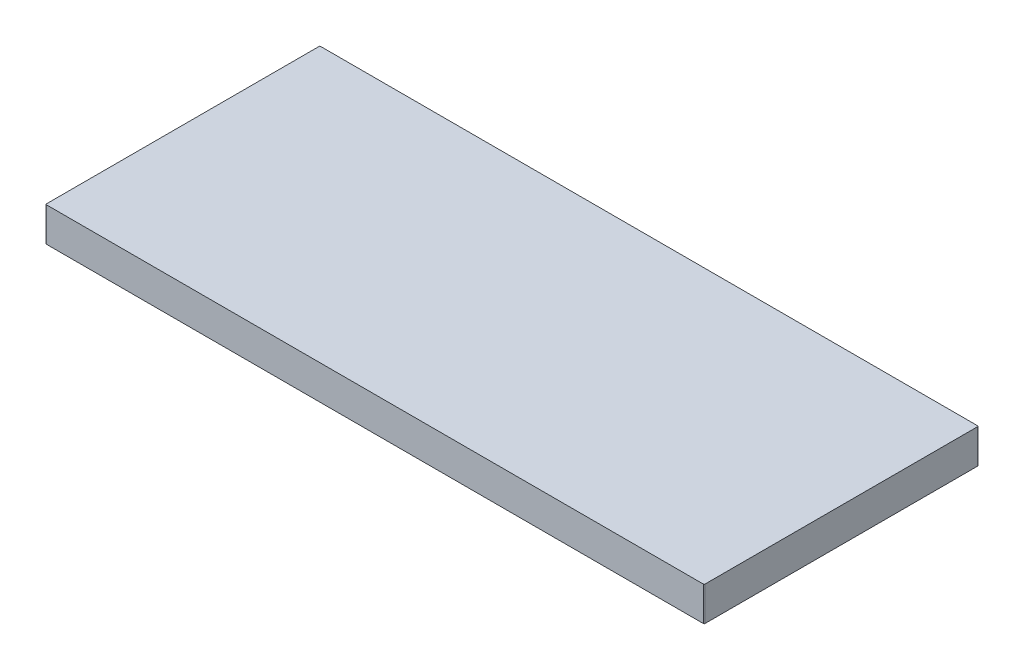
SolidWorks part; units mm, degrees
ref_plane "Front Plane" through (0, 0, 0) normal (0, 0, 1) x (1, 0, 0)
ref_plane "Top Plane" through (0, 0, 0) normal (0, 1, 0) x (1, 0, 0)
ref_plane "Right Plane" through (0, 0, 0) normal (1, 0, 0) x (0, 0, -1)
sketch "Sketch1" plane through (0, 0, 0) normal (0, 1, 0) x (1, 0, 0)
  line L1 (-48.15, -20.05) -> (48.15, -20.05)
  line L2 (-48.15, -20.05) -> (-48.15, 20.05)
  line L3 (-48.15, 20.05) -> (48.15, 20.05)
  line L4 (48.15, -20.05) -> (48.15, 20.05)
  line L5 (-48.15, -20.05) -> (48.15, 20.05) construction
  line L6 (-48.15, 20.05) -> (48.15, -20.05) construction
  point P0 (0, 0)
  dimension "D1" = 96.3
  dimension "D2" = 40.1
extrude "Boss-Extrude1" add sketch "Sketch1" along normal blind 5
fillet "Fillet1" radius 0.1 4 edges at (48.15, 2.5, -20.05) (48.15, 2.5, 20.05) (-48.15, 2.5, -20.05) (-48.15, 2.5, 20.05)
